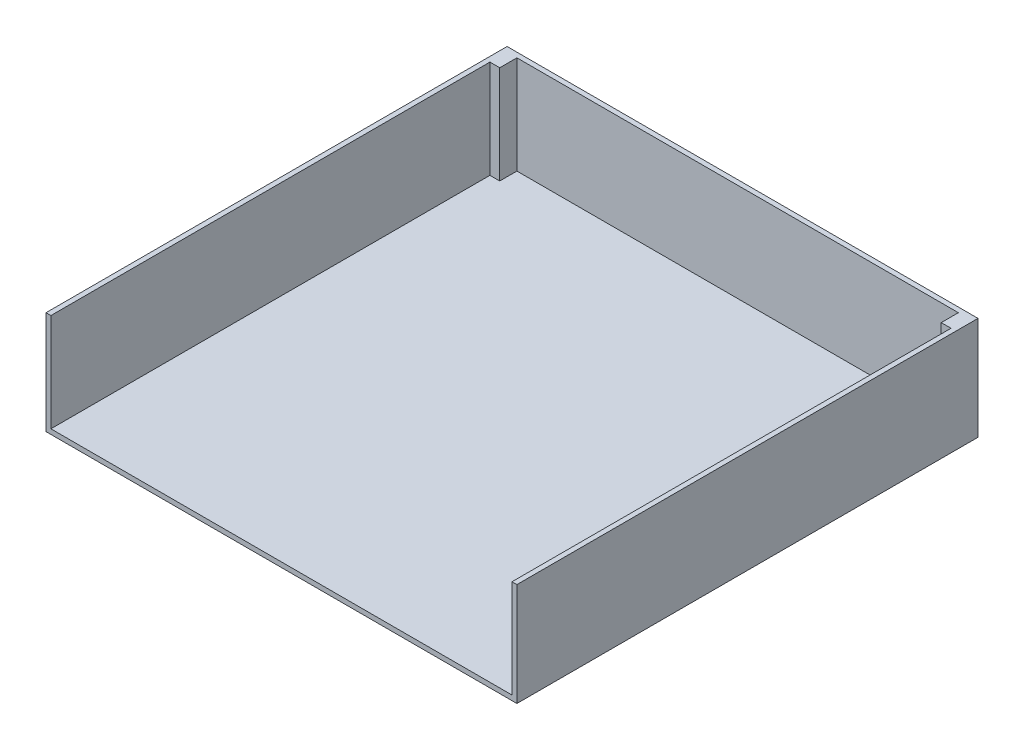
SolidWorks part; units mm, degrees
ref_plane "Front Plane" through (0, 0, 0) normal (0, 0, 1) x (1, 0, 0)
ref_plane "Top Plane" through (0, 0, 0) normal (0, 1, 0) x (1, 0, 0)
ref_plane "Right Plane" through (0, 0, 0) normal (1, 0, 0) x (0, 0, -1)
sketch "Sketch1" plane through (0, 0, 0) normal (0, 1, 0) x (1, 0, 0)
  line L0 (-596.9, -584.2) -> (-596.9, 584.2)
  line L1 (-609.6, -596.9) -> (-596.9, -596.9)
  line L2 (-609.6, -596.9) -> (-609.6, 596.9)
  line L3 (-609.6, 596.9) -> (609.6, 596.9)
  line L4 (609.6, -596.9) -> (609.6, 596.9)
  line L5 (-609.6, -596.9) -> (609.6, 596.9) construction
  line L6 (-609.6, 596.9) -> (609.6, -596.9) construction
  line L7 (-596.9, 584.2) -> (596.9, 584.2)
  line L8 (596.9, -584.2) -> (596.9, 584.2)
  line L9 (596.9, -596.9) -> (609.6, -596.9)
  line L10 (-596.9, -584.2) -> (-596.9, -596.9)
  line L11 (596.9, -584.2) -> (596.9, -596.9)
  line L13 (-596.9, -584.2) -> (596.9, -584.2) construction
  line L14 (-609.6, -596.9) -> (609.6, -596.9) construction
  point P0 (0, 0)
  dimension "D1" = 1219.2
  dimension "D2" = 1193.8
  dimension "D3" = 12.7
extrude "Boss-Extrude1" add sketch "Sketch1" along normal blind 254
sketch "Sketch2" plane through (0, 0, 0) normal (0, -1, 0) x (1, 0, 0)
  line L1 (609.6, -596.9) -> (-609.6, -596.9)
  line L2 (609.6, -596.9) -> (609.6, 596.9)
  line L3 (609.6, 596.9) -> (-609.6, 596.9)
  line L4 (-609.6, -596.9) -> (-609.6, 596.9)
extrude "Boss-Extrude2" add sketch "Sketch2" along normal blind 12.7
sketch "Sketch3" plane through (0, 0, 0) normal (0, 1, 0) x (1, 0, 0)
  line L1 (-596.9, 584.2) -> (-571.5, 584.2)
  line L2 (-596.9, 584.2) -> (-596.9, 539.75)
  line L3 (-596.9, 539.75) -> (-571.5, 539.75)
  line L4 (-571.5, 584.2) -> (-571.5, 539.75)
  line L5 (596.9, 584.2) -> (571.5, 584.2)
  line L6 (596.9, 584.2) -> (596.9, 539.75)
  line L7 (596.9, 539.75) -> (571.5, 539.75)
  line L8 (571.5, 584.2) -> (571.5, 539.75)
  dimension "D1" = 25.4
  dimension "D2" = 44.45
  dimension "D3" = 44.45
  dimension "D4" = 25.4
extrude "Boss-Extrude3" add sketch "Sketch3" along normal blind 254
